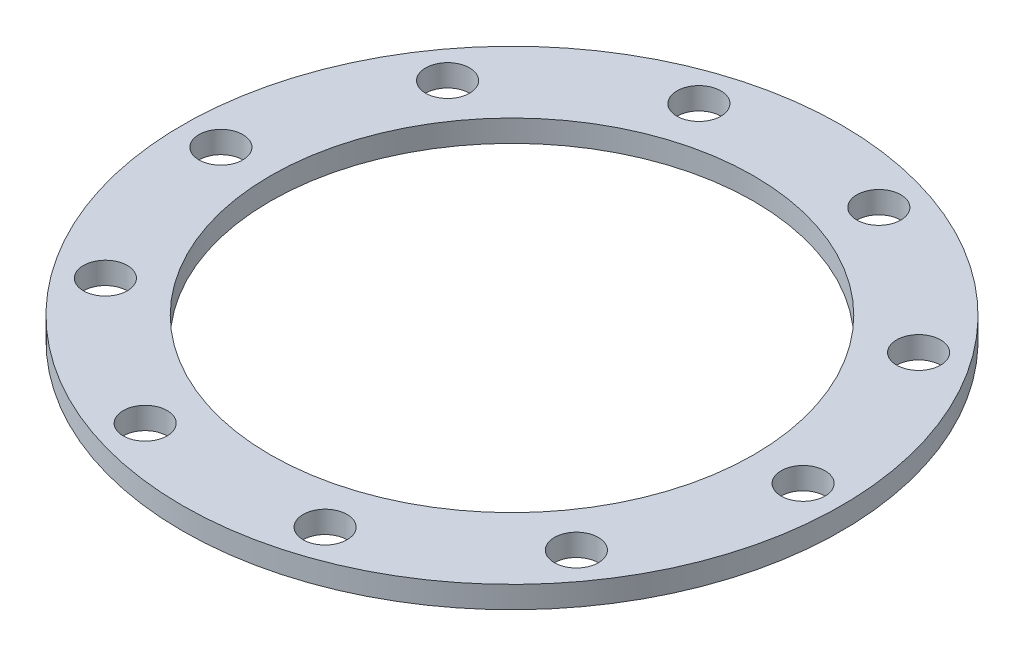
SolidWorks part; units mm, degrees
ref_plane "Front Plane" through (0, 0, 0) normal (0, 0, 1) x (1, 0, 0)
ref_plane "Top Plane" through (0, 0, 0) normal (0, 1, 0) x (1, 0, 0)
ref_plane "Right Plane" through (0, 0, 0) normal (1, 0, 0) x (0, 0, -1)
sketch "Sketch1" plane through (0, 0, 0) normal (0, 1, 0) x (1, 0, 0)
  circle A0 centre (0, 0) radius 76.2
  circle A1 centre (0, 0) radius 55.88
  dimension "D1" = 152.4
  dimension "D2" = 20.32
extrude "Boss-Extrude1" add sketch "Sketch1" along normal blind 5.08
sketch "Sketch2" plane through (0, 5.08, 0) normal (0, 1, 0) x (1, 0, 0)
  line L0 (0, 0) -> (-67.31, 0) construction
  circle A0 centre (-67.31, 0) radius 5.08
  dimension "D2" = 10.16
  dimension "D1" = 67.31
extrude "Cut-Extrude1" cut sketch "Sketch2" against normal through all
pattern_circular "CirPattern1" count 10 over 360 about axis through (0, 0, 0) along (0, 1, 0) of "Cut-Extrude1"
